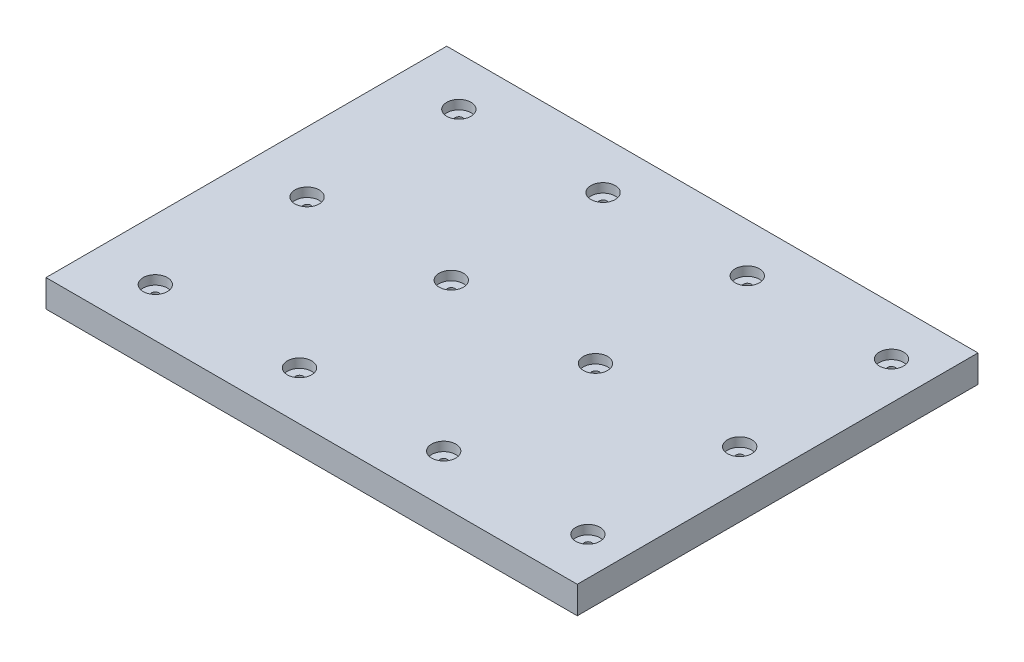
SolidWorks part; units mm, degrees
ref_plane "Front Plane" through (0, 0, 0) normal (0, 0, 1) x (1, 0, 0)
ref_plane "Top Plane" through (0, 0, 0) normal (0, 1, 0) x (1, 0, 0)
ref_plane "Right Plane" through (0, 0, 0) normal (1, 0, 0) x (0, 0, -1)
sketch "Sketch2" plane through (0, 0, 0) normal (0, 1, 0) x (1, 0, 0)
  line L5 (0, 0) -> (920, 0)
  line L6 (0, 0) -> (0, 264)
  line L7 (0, 264) -> (920, 264)
  line L8 (920, 0) -> (920, 264)
  dimension "D1" = 264
  dimension "D2" = 920
extrude "Boss-Extrude1" add sketch "Sketch2" along normal blind 18
sketch "Sketch1" plane through (0, 18, 0) normal (0, 1, 0) x (1, 0, 0)
  line L0 (0, 132) -> (920, 132) construction
  line L1 (0, 0) -> (920, 0) construction
  line L2 (0, 0) -> (0, 264) construction
  line L3 (0, 264) -> (920, 264) construction
  line L4 (920, 0) -> (920, 264) construction
  line L5 (40, 264) -> (40, 0) construction
  line L6 (0, 182) -> (920, 182) construction
  line L7 (0, 182) -> (0, 82) construction
  line L8 (0, 82) -> (920, 82) construction
  line L9 (920, 182) -> (920, 82) construction
  line L10 (0, 232) -> (920, 232) construction
  line L11 (0, 232) -> (0, 32) construction
  line L12 (0, 32) -> (920, 32) construction
  line L13 (920, 232) -> (920, 32) construction
  line L14 (0, 157) -> (920, 157) construction
  line L15 (0, 157) -> (0, 107) construction
  line L16 (0, 107) -> (920, 107) construction
  line L17 (920, 157) -> (920, 107) construction
  line L18 (0, 157) -> (920, 157) construction
  line L19 (0, 157) -> (0, 207) construction
  line L20 (0, 207) -> (920, 207) construction
  line L21 (920, 157) -> (920, 207) construction
  line L22 (920, 207) -> (0, 207) construction
  line L23 (920, 207) -> (920, 257) construction
  line L24 (920, 257) -> (0, 257) construction
  line L25 (0, 207) -> (0, 257) construction
  line L26 (0, 107) -> (920, 107) construction
  line L27 (0, 107) -> (0, 57) construction
  line L28 (0, 57) -> (920, 57) construction
  line L29 (920, 107) -> (920, 57) construction
  line L30 (920, 57) -> (0, 57) construction
  line L31 (920, 57) -> (920, 7) construction
  line L32 (920, 7) -> (0, 7) construction
  line L33 (0, 57) -> (0, 7) construction
  circle A0 centre (40, 32) radius 2.5
  circle A1 centre (135, 32) radius 2.5
  circle A2 centre (230, 32) radius 2.5
  circle A3 centre (325, 32) radius 2.5
  circle A4 centre (420, 32) radius 2.5
  circle A5 centre (515, 32) radius 2.5
  circle A6 centre (610, 32) radius 2.5
  circle A7 centre (705, 32) radius 2.5
  circle A8 centre (800, 32) radius 2.5
  circle A9 centre (895, 32) radius 2.5
  circle A10 centre (135, 132) radius 2.5
  circle A11 centre (230, 132) radius 2.5
  circle A12 centre (325, 132) radius 2.5
  circle A13 centre (420, 132) radius 2.5
  circle A14 centre (515, 132) radius 2.5
  circle A15 centre (610, 132) radius 2.5
  circle A16 centre (705, 132) radius 2.5
  circle A17 centre (800, 132) radius 2.5
  circle A18 centre (895, 132) radius 2.5
  circle A19 centre (135, 232) radius 2.5
  circle A20 centre (230, 232) radius 2.5
  circle A21 centre (325, 232) radius 2.5
  circle A22 centre (420, 232) radius 2.5
  circle A23 centre (515, 232) radius 2.5
  circle A24 centre (610, 232) radius 2.5
  circle A25 centre (705, 232) radius 2.5
  circle A26 centre (800, 232) radius 2.5
  circle A27 centre (895, 232) radius 2.5
  circle A28 centre (40, 132) radius 2.5
  circle A29 centre (40, 232) radius 2.5
  dimension "D14" = 5
  dimension "D1" = 264
  dimension "D2" = 920
  dimension "D3" = 50
  dimension "D4" = 50
  dimension "D5" = 50
  dimension "D6" = 50
  dimension "D7" = 50
  dimension "D8" = 50
  dimension "D9" = 50
  dimension "D10" = 50
  dimension "D11" = 50
  dimension "D12" = 25
  dimension "D13" = 40
  dimension "D15" = 10
  dimension "D16" = 3
extrude "Cut-Extrude2" cut sketch "Sketch1" against normal blind 18
sketch "Sketch3" plane through (0, 18, 0) normal (0, 1, 0) x (1, 0, 0)
  circle A0 centre (40, 32) radius 8
  circle A1 centre (135, 32) radius 8
  circle A2 centre (230, 32) radius 8
  circle A3 centre (325, 32) radius 8
  circle A4 centre (420, 32) radius 8
  circle A5 centre (515, 32) radius 8
  circle A6 centre (610, 32) radius 8
  circle A7 centre (705, 32) radius 8
  circle A8 centre (800, 32) radius 8
  circle A9 centre (895, 32) radius 8
  circle A10 centre (135, 132) radius 8
  circle A11 centre (230, 132) radius 8
  circle A12 centre (325, 132) radius 8
  circle A13 centre (420, 132) radius 8
  circle A14 centre (515, 132) radius 8
  circle A15 centre (610, 132) radius 8
  circle A16 centre (705, 132) radius 8
  circle A17 centre (800, 132) radius 8
  circle A18 centre (895, 132) radius 8
  circle A19 centre (135, 232) radius 8
  circle A20 centre (230, 232) radius 8
  circle A21 centre (325, 232) radius 8
  circle A22 centre (420, 232) radius 8
  circle A23 centre (515, 232) radius 8
  circle A24 centre (610, 232) radius 8
  circle A25 centre (705, 232) radius 8
  circle A26 centre (800, 232) radius 8
  circle A27 centre (895, 232) radius 8
  circle A28 centre (40, 132) radius 8
  circle A29 centre (40, 232) radius 8
  dimension "D1" = 16
  dimension "D2" = 10
  dimension "D3" = 3
extrude "Cut-Extrude3" cut sketch "Sketch3" against normal blind 6
sketch "Sketch4" plane through (0, 18, 0) normal (0, 1, 0) x (1, 0, 0)
  line L0 (0, 0) -> (920, 0) construction
  line L1 (920, 264) -> (350, 264)
  line L2 (920, 264) -> (920, 0)
  line L3 (920, 0) -> (350, 0)
  line L4 (350, 264) -> (350, 0)
  line L5 (0, 264) -> (0, 0) construction
  dimension "D1" = 350
extrude "Cut-Extrude4" cut sketch "Sketch4" against normal blind 20
sketch "Sketch5" plane through (0, 18, 0) normal (0, 1, 0) x (1, 0, 0)
  line L0 (175, 264) -> (175, 0) construction
  line L1 (175, 132) -> (350, 132) construction
  line L2 (175, 132) -> (-273, 132) construction
  line L3 (0, 264) -> (-273, 264) construction
  line L4 (0, 0) -> (350, 0)
  line L5 (350, 0) -> (350, 264)
  line L6 (350, 264) -> (0, 264)
  line L7 (0, 264) -> (0, 0)
  line L8 (0, 0) -> (350, 0)
  line L9 (350, 0) -> (350, 264)
  line L10 (350, 264) -> (0, 264)
  line L11 (0, 264) -> (0, 0)
  line L12 (-273, 264) -> (-273, 132) construction
  line L13 (-273, 132) -> (-273, 0) construction
  line L14 (-273, 0) -> (0, 0) construction
  dimension "D2" = 448
  dimension "D3" = 350
  dimension "D4" = 264
  dimension "D1" = 0
